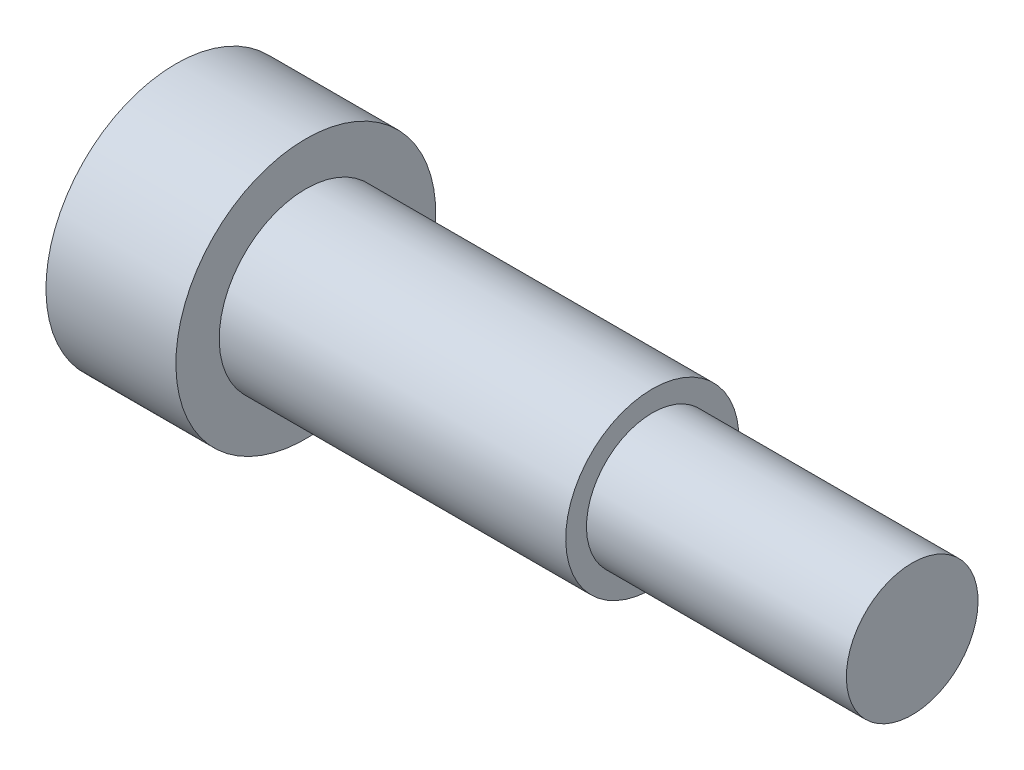
SolidWorks part; units mm, degrees
ref_plane "Front Plane" through (0, 0, 0) normal (0, 0, 1) x (1, 0, 0)
ref_plane "Top Plane" through (0, 0, 0) normal (0, 1, 0) x (1, 0, 0)
ref_plane "Right Plane" through (0, 0, 0) normal (1, 0, 0) x (0, 0, -1)
sketch "Sketch1" plane through (0, 0, 0) normal (0, 0, 1) x (1, 0, 0)
  line L0 (0, 4.7625) -> (4.7625, 4.7625)
  line L1 (4.7625, 4.7625) -> (4.7625, 3.175)
  line L2 (4.7625, 3.175) -> (17.4625, 3.175)
  line L3 (17.4625, 3.175) -> (17.4625, 2.413)
  line L4 (17.4625, 2.413) -> (26.9875, 2.413)
  line L5 (26.9875, 2.413) -> (26.9875, 0)
  line L6 (26.9875, 0) -> (0, 0)
  line L7 (0, 0) -> (0, 4.7625)
  dimension "Head Ht" = 4.7625
  dimension "Thread Lg" = 9.525
  dimension "Shoulder Lg" = 12.7
  dimension "D1" = 4.7625
revolve "Revolve1" add sketch "Sketch1" angle 360 about L6
